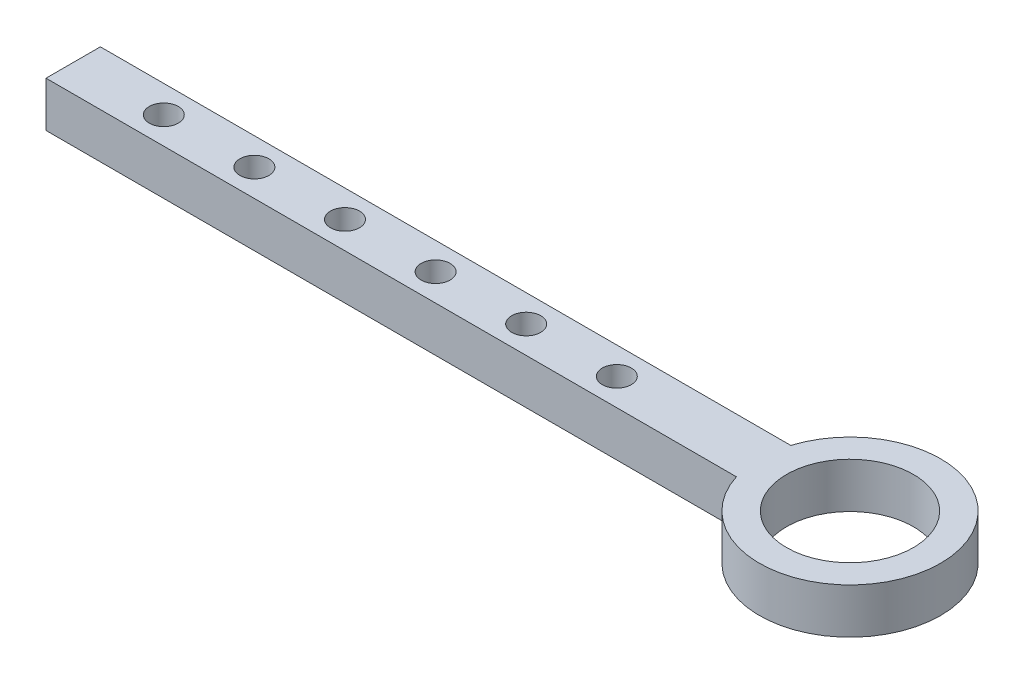
SolidWorks part; units mm, degrees
ref_plane "Front" through (0, 0, 0) normal (0, 0, 1) x (1, 0, 0)
ref_plane "Top" through (0, 0, 0) normal (0, 1, 0) x (1, 0, 0)
ref_plane "Right" through (0, 0, 0) normal (1, 0, 0) x (0, 0, -1)
sketch "Sketch1" plane through (0, 0, 0) normal (0, 1, 0) x (1, 0, 0)
  line L0 (0, 3) -> (76.2, 3)
  line L1 (0, 0) -> (76.2, 0)
  line L2 (0, 0) -> (0, 6)
  line L3 (0, 6) -> (76.2, 6)
  line L4 (76.2, 0) -> (76.2, 6)
  circle A0 centre (85.7394, 3) radius 10
  circle A1 centre (85.7394, 3) radius 7
  circle A2 centre (10, 3) radius 1.6
  circle A3 centre (20, 3) radius 1.6
  circle A4 centre (30, 3) radius 1.6
  circle A5 centre (40, 3) radius 1.6
  circle A6 centre (50, 3) radius 1.6
  circle A7 centre (60, 3) radius 1.6
  dimension "D3" = 10
  dimension "D1" = 6
  dimension "D2" = 76.2
  dimension "D4" = 6
extrude "Boss-Extrude1" add sketch "Sketch1" along normal blind 5 contours L4 A0 A1 | L4 A0 L0 | L0 A0 L4 | A7 L0 A6 A5 A4 A3 A2 L2 L1 A0 | A7 L0 A0 L3 L2 A2 A3 A4 A5 A6
